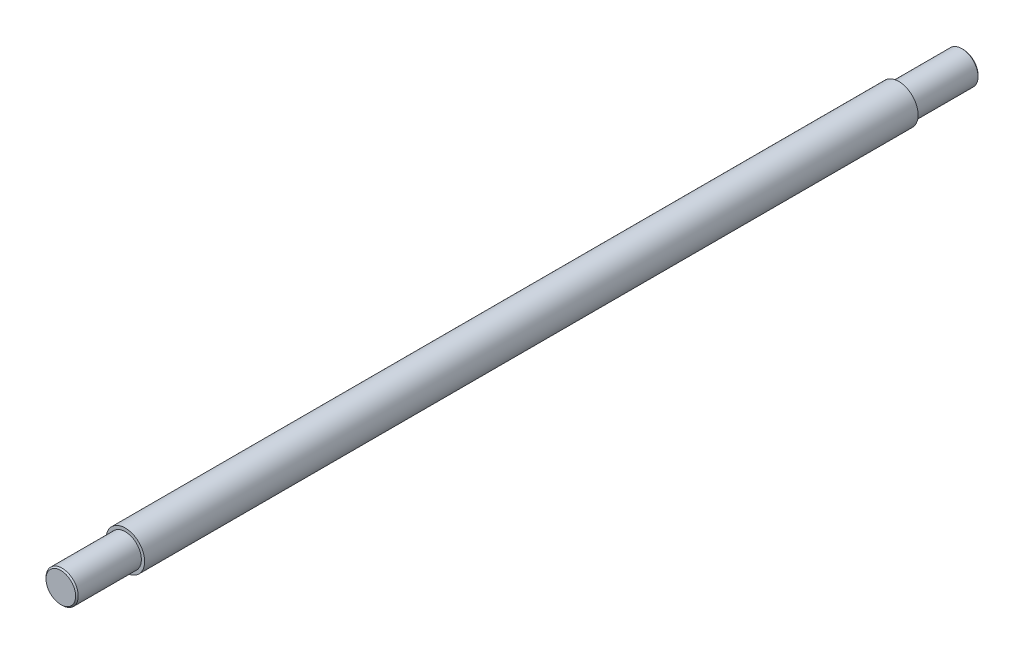
SolidWorks part; units mm, degrees
ref_plane "Front Plane" through (0, 0, 0) normal (0, 0, 1) x (1, 0, 0)
ref_plane "Top Plane" through (0, 0, 0) normal (0, 1, 0) x (1, 0, 0)
ref_plane "Right Plane" through (0, 0, 0) normal (1, 0, 0) x (0, 0, -1)
ref_plane "Plane1" through (0, 0, 0) normal (0, -1, 0) x (1, 0, 0)
sketch "Sketch1" plane through (0, 0, 0) normal (0, -1, 0) x (1, 0, 0)
  line L0 (2.3, 70) -> (0, 70)
  line L1 (0, 70) -> (0, -70)
  line L2 (0, -70) -> (2.3, -70)
  line L3 (2.3, -70) -> (2.5, -69.8)
  line L4 (2.5, -69.8) -> (2.5, -60)
  line L5 (2.5, -60) -> (3, -60)
  line L6 (3, -60) -> (3, 60)
  line L7 (3, 60) -> (2.5, 60)
  line L8 (2.5, 60) -> (2.5, 69.8)
  line L9 (2.5, 69.8) -> (2.3, 70)
  line L10 (0, 70) -> (0, -70) construction
revolve "Revolve1" add sketch "Sketch1" angle 360 about L10
